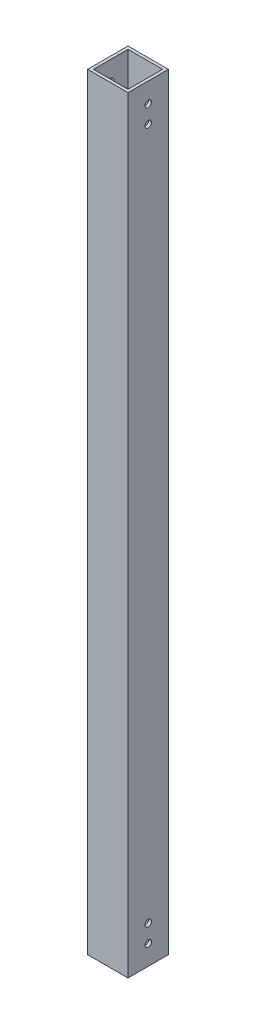
SolidWorks part; units mm, degrees
material "6061 Alloy"
ref_plane "Front Plane" through (0, 0, 0) normal (0, 0, 1) x (1, 0, 0)
ref_plane "Top Plane" through (0, 0, 0) normal (0, 1, 0) x (1, 0, 0)
ref_plane "Right Plane" through (0, 0, 0) normal (1, 0, 0) x (0, 0, -1)
sketch "Sketch1" plane through (0, 0, 0) normal (0, 1, 0) x (1, 0, 0)
  line L0 (-19.05, -19.05) -> (-19.05, 19.05)
  line L1 (-22.225, -22.225) -> (22.225, -22.225)
  line L2 (-22.225, -22.225) -> (-22.225, 22.225)
  line L3 (-22.225, 22.225) -> (22.225, 22.225)
  line L4 (22.225, -22.225) -> (22.225, 22.225)
  line L5 (-22.225, -22.225) -> (22.225, 22.225) construction
  line L6 (-22.225, 22.225) -> (22.225, -22.225) construction
  line L7 (-19.05, 19.05) -> (19.05, 19.05)
  line L8 (19.05, -19.05) -> (19.05, 19.05)
  line L9 (-19.05, -19.05) -> (19.05, -19.05)
  circle A0 centre (0, 0) radius 21.082 construction
  circle A1 centre (0, 0) radius 17.526 construction
  dimension "D1" = 42.164
  dimension "D3" = 44.45
  dimension "D2" = 3.556
  dimension "D4" = 3.175
extrude "Boss-Extrude1" add sketch "Sketch1" along normal blind 844.55
chamfer "Chamfer1" [suppressed] distance 1.5875 angle 45
hole_wizard "1/4 Clearance Hole1" positions "Sketch2" profile "Sketch3" hole size "1/4" standard "ANSI Inch" end condition through all
sketch "Sketch2" plane through (-22.225, 0, 0) normal (-1, 0, 0) x (0, 0, 1)
  line L0 (0, 844.55) -> (0, 0) construction
  line L1 (-22.225, 844.55) -> (22.225, 844.55) construction
  line L2 (-22.225, 0) -> (22.225, 0) construction
  line L4 (-22.225, 422.275) -> (22.225, 422.275) construction
  line L5 (-22.225, 844.55) -> (-22.225, 0) construction
  line L6 (22.225, 844.55) -> (22.225, 0) construction
  point P0 (0, 803.275)
  point P17 (0, 41.275)
  point P18 (0, 822.7219)
  point P21 (0, 21.8281)
  dimension "D1" = 41.275
  dimension "D2" = 21.8281
sketch "Sketch3" plane through (-22.225, 803.275, 0) normal (0, 1, 0) x (0, 0, 1)
  line L0 (0, 0) -> (0, 44.45)
  line L1 (0, 44.45) -> (3.5712, 44.45)
  line L2 (3.5712, 44.45) -> (3.5712, 0)
  line L5 (3.5712, 0) -> (0, 0)
  line L11 (0, -6.35) -> (0, 107.95) construction
  dimension "Thru Hole Dia." = 7.1425
  dimension "Thru Hole Depth" = 44.45
equation "\"D1@Boss-Extrude1\"=36-2.75"
